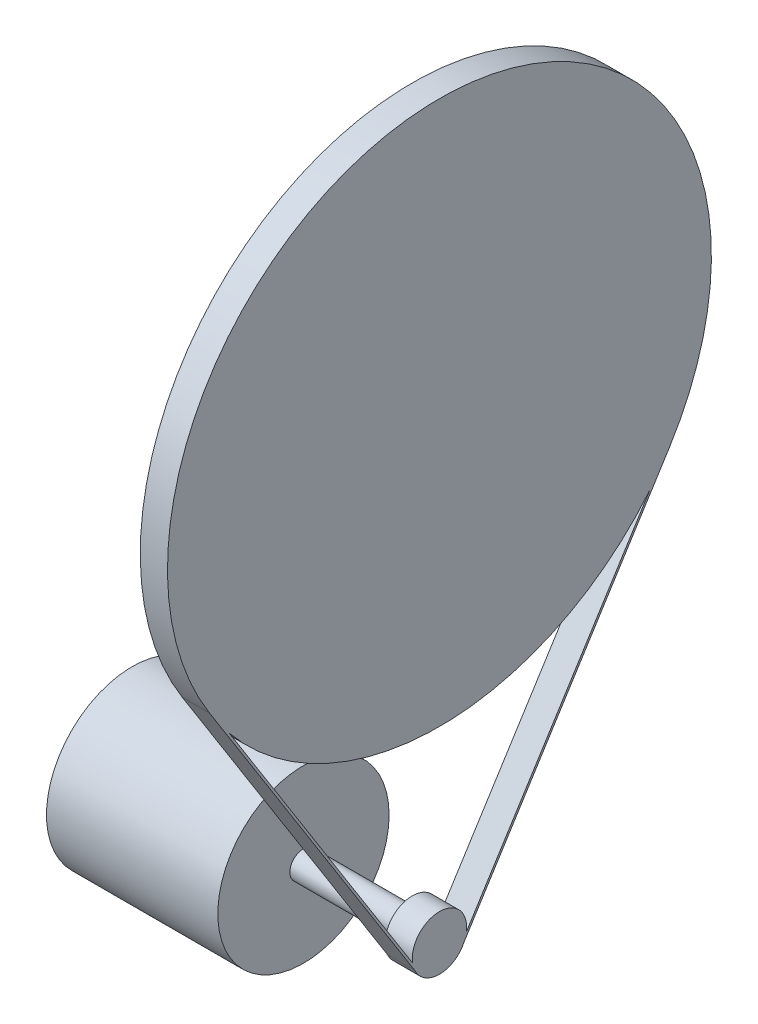
SolidWorks part; units mm, degrees
ref_plane "Front" through (0, 0, 0) normal (0, 0, 1) x (1, 0, 0)
ref_plane "Top" through (0, 0, 0) normal (0, 1, 0) x (1, 0, 0)
ref_plane "Right" through (0, 0, 0) normal (1, 0, 0) x (0, 0, -1)
sketch "Croquis1" plane through (0, 0, 0) normal (1, 0, 0) x (0, 0, -1)
  circle A0 centre (0, 0) radius 40
  dimension "D1" = 80
extrude "Saliente-Extruir1" add sketch "Croquis1" along normal blind 80
sketch "Croquis2" plane through (80, 0, 0) normal (1, 0, 0) x (0, 0, -1)
  circle A0 centre (0, 0) radius 6.35
  dimension "D1" = 12.7
extrude "Saliente-Extruir2" add sketch "Croquis2" along normal blind 50.8
sketch "Croquis3" plane through (130.8, 0, 0) normal (1, 0, 0) x (0, 0, -1)
  circle A0 centre (0, 0) radius 12.7
  dimension "D1" = 25.4
extrude "Saliente-Extruir3" add sketch "Croquis3" along normal blind 12.7
sketch "Croquis4" plane through (130.8, 0, 0) normal (-1, 0, 0) x (0, 0, 1)
  line L0 (0, 0) -> (0, 214.4783) construction
  line L1 (11.484, -5.423) -> (107.4281, 146.742)
  line L2 (12.5675, -1.8295) -> (98.0986, 133.8206)
  line L3 (10.6381, -4.8896) -> (106.5822, 147.2754) construction
  line L4 (-12.5675, -1.8295) -> (-98.0986, 133.8206)
  line L5 (-11.484, -5.423) -> (-107.4281, 146.742)
  arc A0 (107.4281, 146.742) -> (-107.4281, 146.742) centre (0, 214.4783) ccw
  circle A1 centre (0, 0) radius 12.7 construction
  arc A2 (12.5675, -1.8295) -> (-12.5675, -1.8295) centre (0, 0) ccw
  arc A3 (-11.484, -5.423) -> (11.484, -5.423) centre (0, 0) ccw
  arc A4 (-98.0986, 133.8206) -> (98.0986, 133.8206) centre (0, 214.4783) ccw
  dimension "D2" = 127
  dimension "D1" = 1
extrude "Saliente-Extruir4" add sketch "Croquis4" against normal blind 12.7
